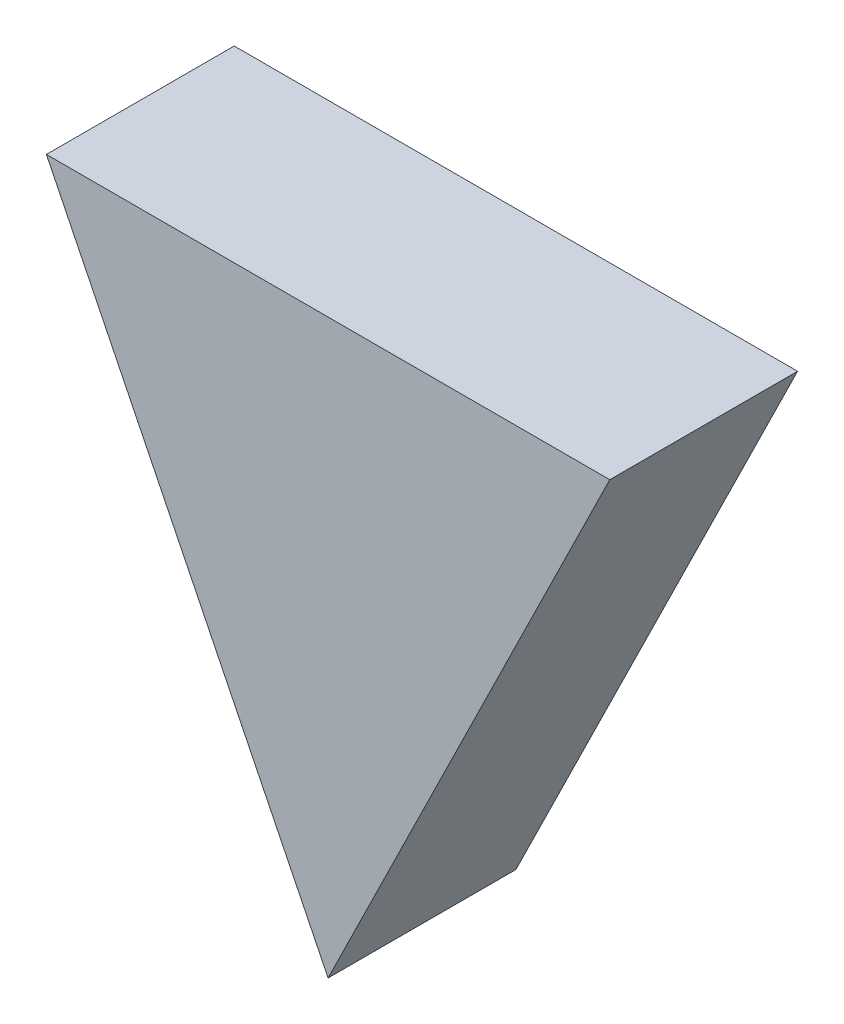
SolidWorks part; units mm, degrees
ref_plane "Front Plane" through (0, 0, 0) normal (0, 0, 1) x (1, 0, 0)
ref_plane "Top Plane" through (0, 0, 0) normal (0, 1, 0) x (1, 0, 0)
ref_plane "Right Plane" through (0, 0, 0) normal (1, 0, 0) x (0, 0, -1)
sketch "Sketch2" plane through (0, 0, 0) normal (0, 0, 1) x (1, 0, 0)
  line L0 (0, 0) -> (15, 30.48)
  line L1 (15, 30.48) -> (-15, 30.48)
  line L2 (-15, 30.48) -> (0, 0)
  line L3 (0.0359, -7.5459) -> (0.4527, 26.4225) construction
  point P6 (0, 0)
  dimension "D1" = 30.48
  dimension "D2" = 30
extrude "Boss-Extrude2" add sketch "Sketch2" along normal blind 10
